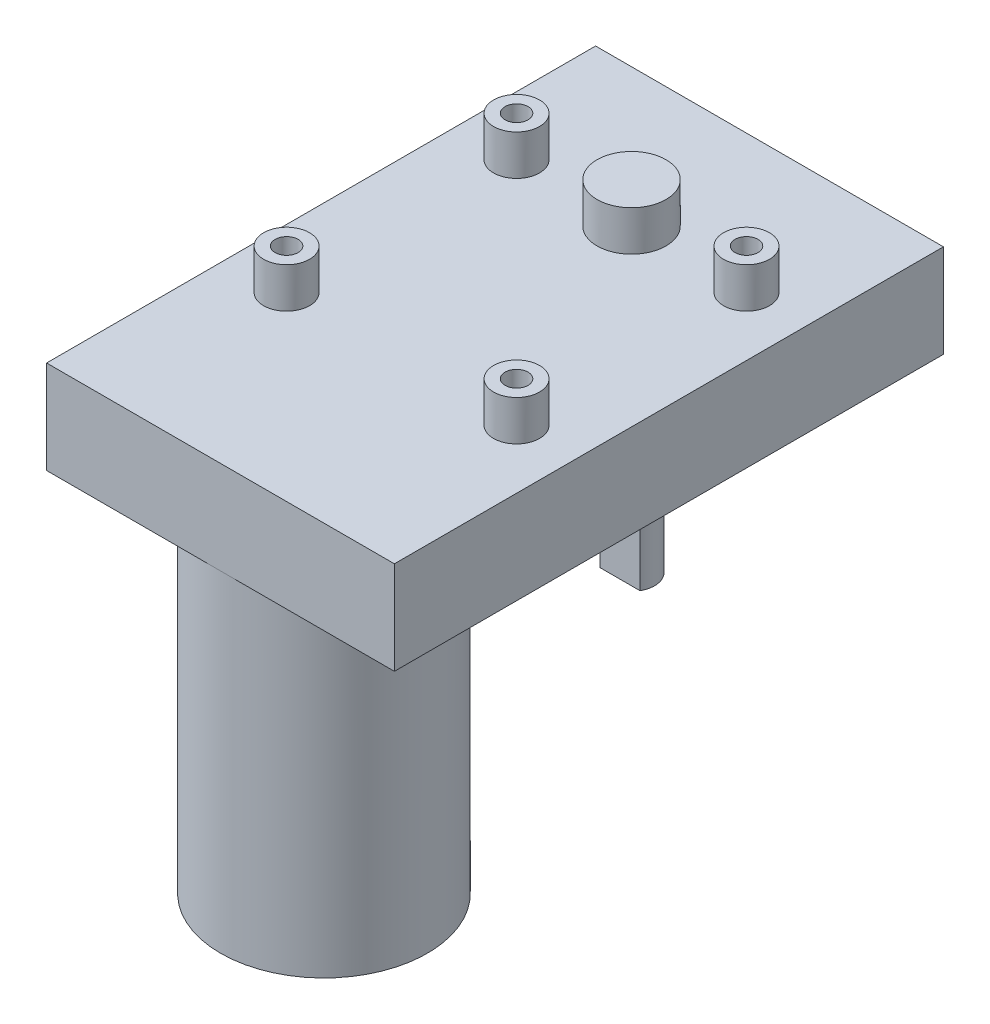
SolidWorks part; units mm, degrees
ref_plane "前视基准面" through (0, 0, 0) normal (0, 0, 1) x (1, 0, 0)
ref_plane "上视基准面" through (0, 0, 0) normal (0, 1, 0) x (1, 0, 0)
ref_plane "右视基准面" through (0, 0, 0) normal (1, 0, 0) x (0, 0, -1)
sketch "草图1" plane through (0, 0, 0) normal (0, 1, 0) x (1, 0, 0)
  line L0 (0, -338.6837) -> (0, 16595.4995) construction
  line L1 (-30.25, -71.5) -> (30.25, -71.5)
  line L2 (-30.25, -71.5) -> (-30.25, 24)
  line L3 (-30.25, 24) -> (30.25, 24)
  line L4 (30.25, -71.5) -> (30.25, 24)
  line L5 (-338.6837, 0) -> (16595.4995, 0) construction
  point P5 (0, 24)
  dimension "D1" = 24
  dimension "D2" = 60.5
  dimension "D4" = 95.5
extrude "凸台-拉伸1" add sketch "草图1" along normal blind 16.2 contours L3 L4 L1 L2
sketch "草图2" plane through (0, 16.2, 0) normal (0, 1, 0) x (1, 0, 0)
  line L0 (-1000, 0) -> (49000, 0) construction
  line L1 (-1000.156, -40) -> (48999.844, -40) construction
  line L2 (0, -1000) -> (0, 49000) construction
  line L3 (-20, 0) -> (-20, -40) construction
  circle A0 centre (0, 0) radius 6
  circle A1 centre (-20, 0) radius 2
  circle A2 centre (20, 0) radius 2
  circle A3 centre (20, -40) radius 2
  circle A4 centre (-20, -40) radius 2
  circle A5 centre (-20, 0) radius 4
  circle A6 centre (20, 0) radius 4
  circle A7 centre (20, -40) radius 4
  circle A8 centre (-20, -40) radius 4
  dimension "D2" = 4
  dimension "D3" = 4
  dimension "D5" = 12
  dimension "D6" = 8
  dimension "D7" = 8
  dimension "D1" = 40
  dimension "D4" = 40
extrude "凸台-拉伸2" add sketch "草图2" along normal blind 7
sketch "草图7" plane through (0, 0, 0) normal (0, -1, 0) x (1, 0, 0)
  circle A0 centre (0, 0) radius 6
  circle A1 centre (0, 0) radius 6 construction
extrude "凸台-拉伸6" add sketch "草图7" along normal blind 6
sketch "草图3" plane through (0, -6, 0) normal (0, 1, 0) x (1, 0, 0)
  circle A0 centre (0, 0) radius 4
  dimension "D1" = 8
extrude "凸台-拉伸3" add sketch "草图3" against normal blind 30
sketch "草图4" plane through (0, -36, 0) normal (0, -1, 0) x (-1, 0, 0)
  line L0 (-3.4641, -2) -> (3.4641, -2)
  circle A0 centre (0, 0) radius 4 construction
  arc A1 (-3.4641, -2) -> (3.4641, -2) centre (0, 0) ccw
  dimension "D1" = 2
extrude "切除-拉伸1" cut sketch "草图4" against normal blind 16
sketch "草图5" plane through (0, 0, 0) normal (0, -1, 0) x (-1, 0, 0)
  line L1 (17.5, 12.5) -> (-17.5, 12.5) construction
  line L2 (17.5, 12.5) -> (17.5, -12.5) construction
  line L3 (17.5, -12.5) -> (-17.5, -12.5) construction
  line L4 (-17.5, 12.5) -> (-17.5, -12.5) construction
  line L5 (17.5, 12.5) -> (-17.5, -12.5) construction
  line L6 (17.5, -12.5) -> (-17.5, 12.5) construction
  circle A0 centre (17.5, -12.5) radius 2
  circle A1 centre (-17.5, -12.5) radius 2
  circle A2 centre (-17.5, 12.5) radius 2
  circle A3 centre (17.5, 12.5) radius 2
  circle A4 centre (-17.5, 12.5) radius 4
  circle A5 centre (17.5, 12.5) radius 4
  circle A6 centre (17.5, -12.5) radius 4
  circle A7 centre (-17.5, -12.5) radius 4
  point P0 (0, 0)
  dimension "D3" = 4
  dimension "D4" = 4
  dimension "D5" = 4
  dimension "D6" = 4
  dimension "D7" = 8
  dimension "D8" = 8
  dimension "D9" = 8
  dimension "D10" = 8
  dimension "D1" = 35
  dimension "D2" = 25
extrude "凸台-拉伸4" add sketch "草图5" along normal blind 8
sketch "草图6" plane through (0, 0, 0) normal (0, -1, 0) x (1, 0, 0)
  line L0 (0, 53.5) -> (0, 0) construction
  line L1 (-30.25, 71.5) -> (30.25, 71.5) construction
  circle A0 centre (0, 53.5) radius 18
  dimension "D1" = 36
extrude "凸台-拉伸5" add sketch "草图6" along normal blind 57.6
